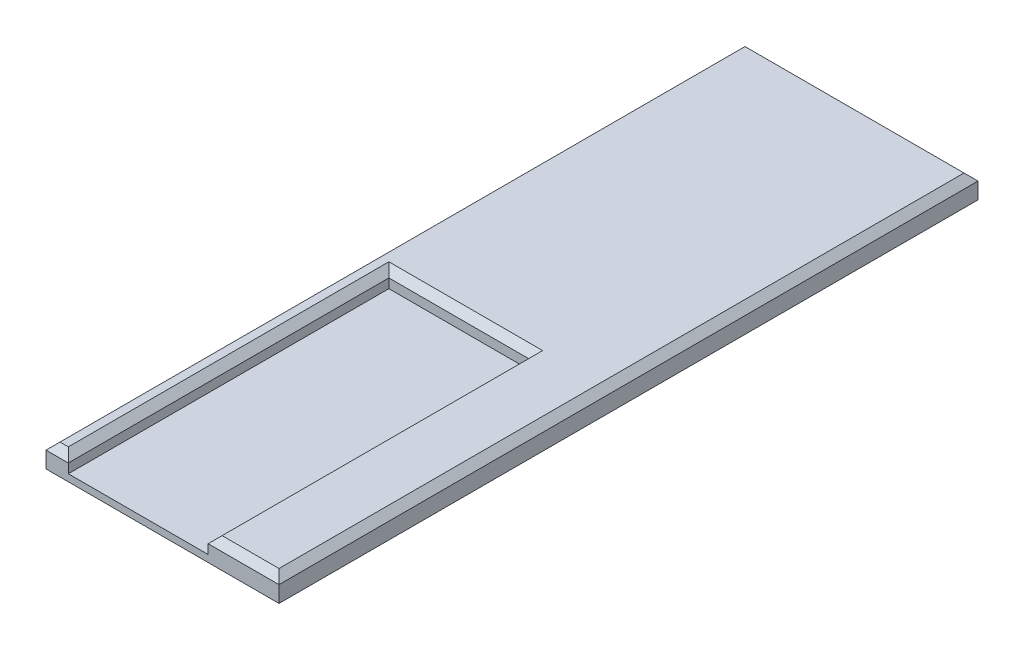
SolidWorks part; units mm, degrees
ref_plane "Front Plane" through (0, 0, 0) normal (0, 0, 1) x (1, 0, 0)
ref_plane "Top Plane" through (0, 0, 0) normal (0, 1, 0) x (1, 0, 0)
ref_plane "Right Plane" through (0, 0, 0) normal (1, 0, 0) x (0, 0, -1)
sketch "Sketch1" plane through (0, 0, 0) normal (0, 1, 0) x (1, 0, 0)
  line L1 (50, -150) -> (-50, -150)
  line L2 (50, -150) -> (50, 150)
  line L3 (50, 150) -> (-50, 150)
  line L4 (-50, -150) -> (-50, 150)
  line L5 (50, -150) -> (-50, 150) construction
  line L6 (50, 150) -> (-50, -150) construction
  point P0 (0, 0)
  dimension "D1" = 100
  dimension "D2" = 300
extrude "Boss-Extrude1" add sketch "Sketch1" against normal blind 10
sketch "Sketch2" plane through (0, 0, 0) normal (0, 1, 0) x (1, 0, 0)
  line L0 (-40.4175, -150) -> (-40.4175, -12.4283)
  line L1 (-40.4175, -12.4283) -> (19.5825, -12.4283)
  line L2 (19.5825, -12.4283) -> (19.5825, -150)
  line L3 (19.5825, -150) -> (-40.4175, -150)
  line L4 (-50, -150) -> (50, -150) construction
  dimension "D1" = 0
extrude "Cut-Extrude1" cut sketch "Sketch2" against normal blind 7
chamfer "Chamfer1" distance 3 angle 45 8 edges at (50, 0, 0) (34.7913, 0, 150) (19.5825, 0, 81.2141) (-10.4175, 0, 12.4283) (-40.4175, 0, 81.2141) (-45.2087, 0, 150) (-50, 0, 0) (0, 0, -150)
